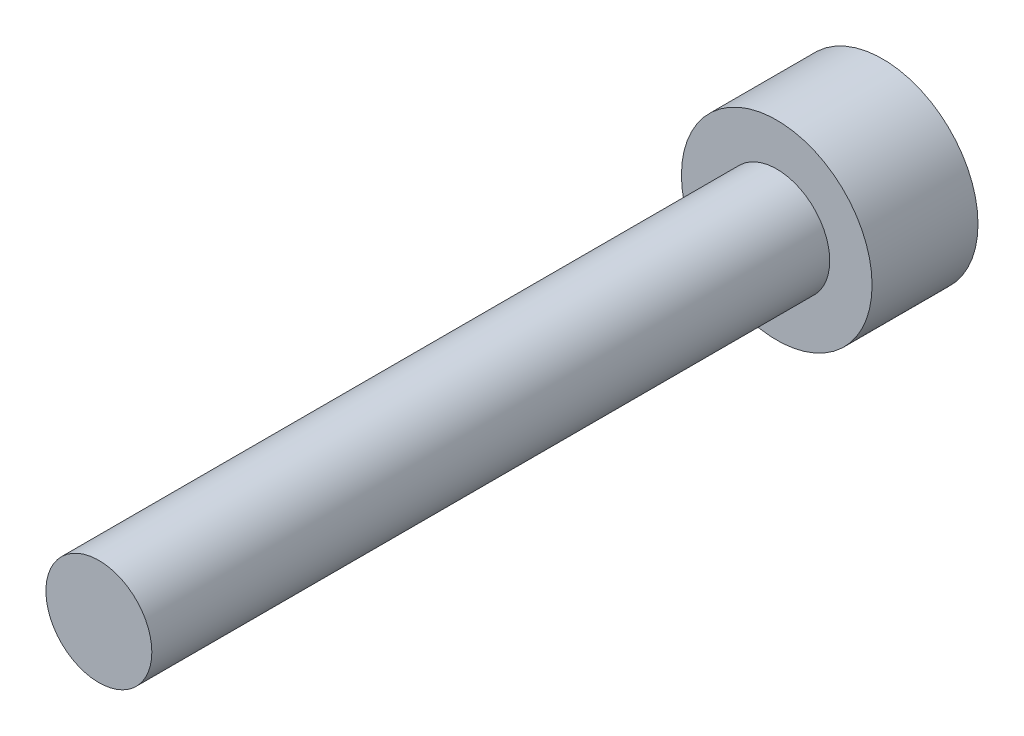
SolidWorks part; units mm, degrees
material "AISI 304"
ref_plane "Alzado" through (0, 0, 0) normal (0, 0, 1) x (1, 0, 0)
ref_plane "Planta" through (0, 0, 0) normal (0, 1, 0) x (1, 0, 0)
ref_plane "Vista lateral" through (0, 0, 0) normal (1, 0, 0) x (0, 0, -1)
sketch "Sk_Cabeza" plane through (0, 0, 0) normal (0, 0, 1) x (1, 0, 0)
  circle A0 centre (0, 0) radius 2.25
  dimension "D1" = 4.5
extrude "Cabeza" add sketch "Sk_Cabeza" along normal blind 2.5 from offset 2.5
sketch "Sk_Cuerpo" plane through (0, 0, 0) normal (0, 0, 1) x (1, 0, 0)
  circle A0 centre (0, 0) radius 1.25
  dimension "D1" = 2.5
extrude "Cuerpo" add sketch "Sk_Cuerpo" along normal blind 16
sketch "Sk_Hexagono_interior" plane through (0, 0, 0) normal (0, 0, 1) x (1, 0, 0)
  line L1 (0, -1.1547) -> (1, -0.5774)
  line L2 (1, -0.5774) -> (1, 0.5774)
  line L3 (1, 0.5774) -> (0, 1.1547)
  line L4 (0, 1.1547) -> (-1, 0.5774)
  line L5 (-1, 0.5774) -> (-1, -0.5774)
  line L6 (-1, -0.5774) -> (0, -1.1547)
  circle A0 centre (0, 0) radius 1 construction
  dimension "D1" = 2
extrude "Hexagono_interior" cut sketch "Sk_Hexagono_interior" along normal blind 1.25 from offset 2.5
